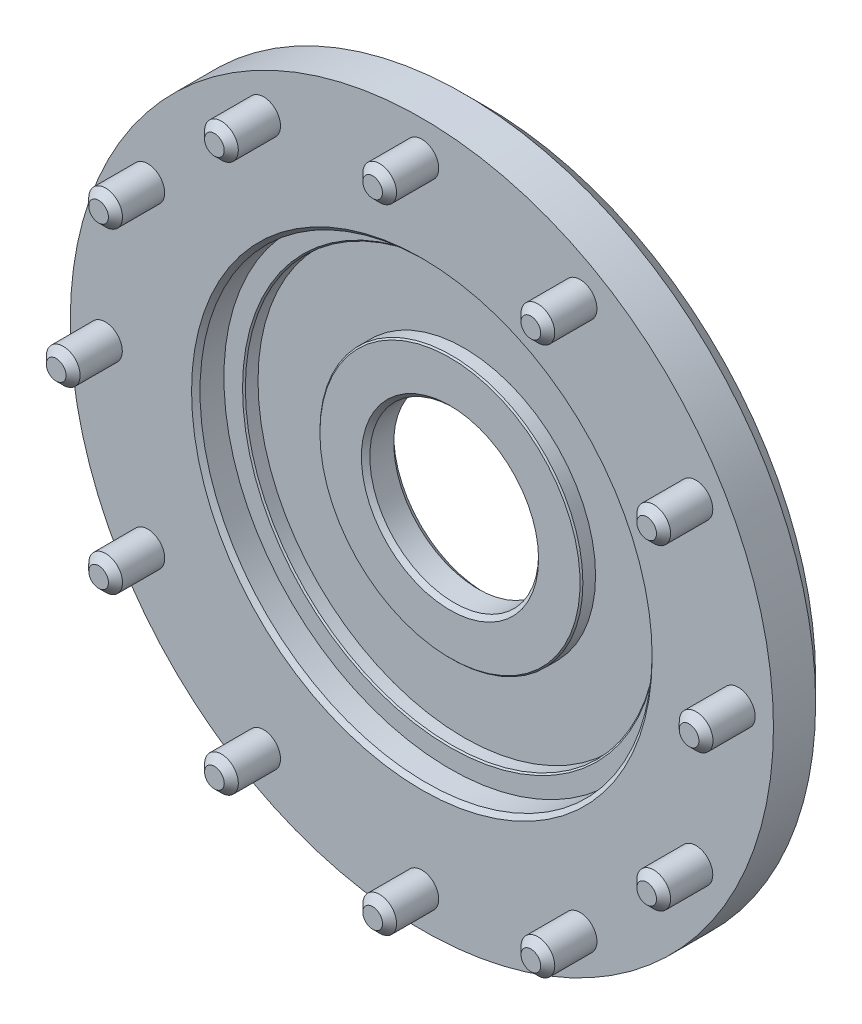
SolidWorks part; units mm, degrees
ref_plane "Front Plane" through (0, 0, 0) normal (0, 0, 1) x (1, 0, 0)
ref_plane "Top Plane" through (0, 0, 0) normal (0, 1, 0) x (1, 0, 0)
ref_plane "Right Plane" through (0, 0, 0) normal (1, 0, 0) x (0, 0, -1)
sketch "Sketch1" plane through (0, 0, 0) normal (0, 0, 1) x (1, 0, 0)
  circle A0 centre (0, 0) radius 50
  dimension "D1" = 100
extrude "Boss-Extrude1" add sketch "Sketch1" against normal blind 9
sketch "Sketch2" plane through (0, 0, 0) normal (0, 0, 1) x (1, 0, 0)
  circle A0 centre (0, 0) radius 45 construction
  circle A1 centre (45, 0) radius 2.4
  dimension "D1" = 90
  dimension "D2" = 4.8
extrude "Boss-Extrude2" add sketch "Sketch2" along normal blind 7
chamfer "Chamfer1" distance 1 angle 45 1 edges at (47.4, 0, 7)
pattern_circular "CirPattern1" count 12 over 360 about axis through (0, 0, 0) along (0, 0, 1) of "Boss-Extrude2", "Chamfer1"
sketch "Sketch3" plane through (0, 0, 0) normal (0, 0, 1) x (1, 0, 0)
  circle A0 centre (0, 0) radius 32.15
  dimension "D1" = 64.3
extrude "Cut-Extrude1" cut sketch "Sketch3" against normal blind 4
sketch "Sketch4" plane through (0, 0, 0) normal (0, 0, 1) x (1, 0, 0)
  circle A0 centre (0, 0) radius 12
  dimension "D1" = 24
extrude "Cut-Extrude2" cut sketch "Sketch4" against normal through all
chamfer "Chamfer2" distance 0.6 angle 45 1 edges at (32.15, 0, 0)
sketch "Sketch5" plane through (0, 0, -4) normal (0, 0, 1) x (1, 0, 0)
  line L0 (-29.3, 0) -> (-18.7, 0) construction
  circle A0 centre (0, 0) radius 24 construction
  circle A1 centre (0, 0) radius 18.7
  circle A2 centre (0, 0) radius 29.3
  point P4 (-24, 0)
  point P8 (-24, 0)
  dimension "D1" = 48
  dimension "D2" = 10.6
extrude "Cut-Extrude3" cut sketch "Sketch5" against normal blind 2
chamfer "Chamfer3" distance 0.2 angle 45 2 edges at (18.7, 0, -4) (29.3, 0, -4)
chamfer "Chamfer4" distance 3 angle 45 1 edges at (50, 0, -9)
chamfer "Chamfer5" distance 1 angle 45 1 edges at (12, 0, -9)
chamfer "Chamfer6" distance 0.6 angle 45 1 edges at (12, 0, -4)
scale "Scale1" scale about centroid uniform scaling yes scale factor 0.4
